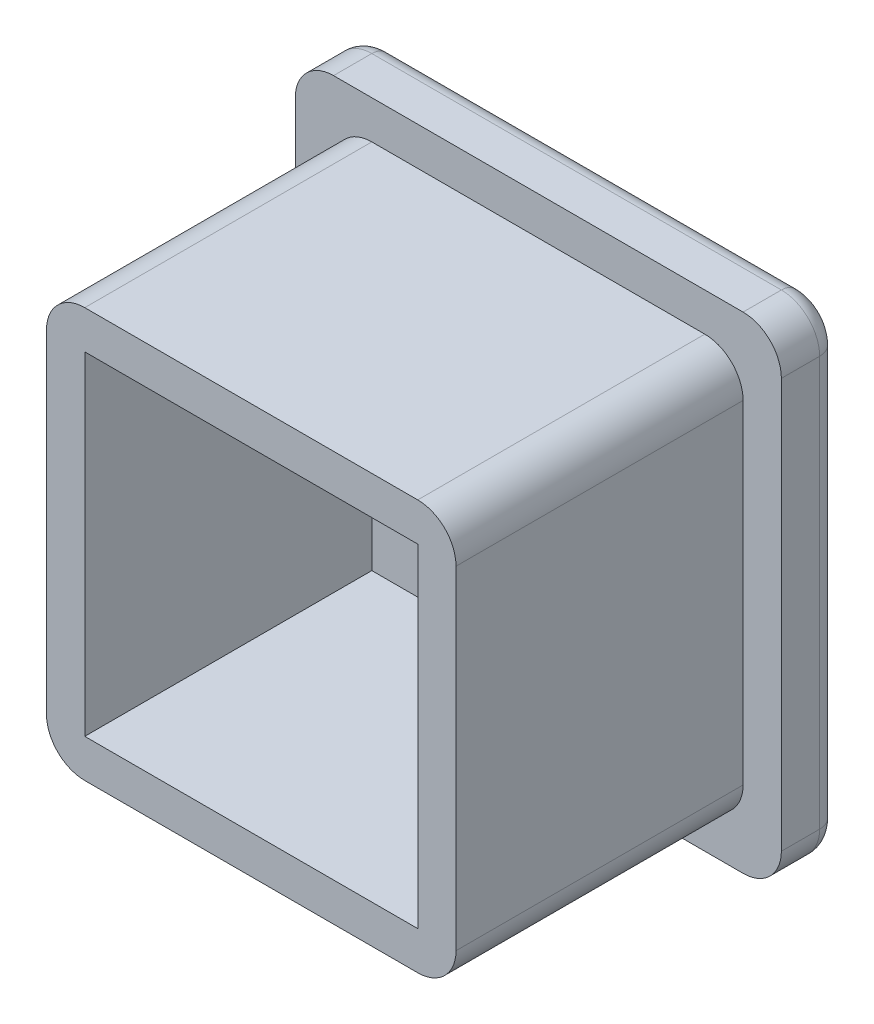
SolidWorks part; units mm, degrees
material "PLA"
ref_plane "Alzado" through (0, 0, 0) normal (0, 0, 1) x (1, 0, 0)
ref_plane "Planta" through (0, 0, 0) normal (0, 1, 0) x (1, 0, 0)
ref_plane "Vista lateral" through (0, 0, 0) normal (1, 0, 0) x (0, 0, -1)
sketch "Croquis1" plane through (0, 0, 0) normal (0, 0, 1) x (1, 0, 0)
  line L1 (12.7, 12.7) -> (-12.7, 12.7)
  line L2 (12.7, 12.7) -> (12.7, -12.7)
  line L3 (12.7, -12.7) -> (-12.7, -12.7)
  line L4 (-12.7, 12.7) -> (-12.7, -12.7)
  line L5 (12.7, 12.7) -> (-12.7, -12.7) construction
  line L6 (12.7, -12.7) -> (-12.7, 12.7) construction
  point P0 (0, 0)
  dimension "D1" = 25.4
  dimension "D2" = 25.4
extrude "Saliente-Extruir1" add sketch "Croquis1" along normal blind 18
sketch "Croquis2" plane through (0, 0, 18) normal (0, 0, 1) x (1, 0, 0)
  line L0 (12.7, 12.7) -> (-12.7, 12.7) construction
  line L1 (-10.7, 10.7) -> (10.7, 10.7)
  line L2 (-10.7, 10.7) -> (-10.7, -10.7)
  line L3 (-10.7, -10.7) -> (10.7, -10.7)
  line L4 (10.7, 10.7) -> (10.7, -10.7)
  line L5 (-12.7, -12.7) -> (12.7, -12.7) construction
  line L6 (-12.7, 12.7) -> (-12.7, -12.7) construction
  line L7 (12.7, -12.7) -> (12.7, 12.7) construction
  line L9 (-12.7, 12.7) -> (12.7, 12.7)
  line L10 (-12.7, 12.7) -> (-12.7, -12.7)
  line L11 (-12.7, -12.7) -> (12.7, -12.7)
  line L12 (12.7, 12.7) -> (12.7, -12.7)
  line L13 (-8.7, 8.7) -> (8.7, 8.7)
  line L14 (-8.7, 8.7) -> (-8.7, -8.7)
  line L15 (-8.7, -8.7) -> (8.7, -8.7)
  line L16 (8.7, 8.7) -> (8.7, -8.7)
  line M9 (-12.7, 12.7) -> (-12.7, -12.7)
  line M10 (-12.7, -12.7) -> (12.7, -12.7)
  line M11 (12.7, -12.7) -> (12.7, 12.7)
  line M12 (12.7, 12.7) -> (-12.7, 12.7)
  dimension "D1" = 2
  dimension "D2" = 2
  dimension "D3" = 2
  dimension "D4" = 2
  dimension "D5" = 4
  dimension "D6" = 4
  dimension "D7" = 4
  dimension "D8" = 4
extrude "Cortar-Extruir1" cut sketch "Croquis2" against normal blind 15 contours L1 L4 L3 L2 M12 M9 M10 M11 | L16 L13 L14 L15
sketch "Croquis3" plane through (0, 0, 18) normal (0, 0, 1) x (1, 0, 0)
  line L0 (-10.7, 10.7) -> (-10.7, -10.7) construction
  line L1 (-10.7, -1.3) -> (-8.7, -1.3)
  line L2 (-10.7, -1.3) -> (-10.7, 1.3)
  line L3 (-10.7, 1.3) -> (-8.7, 1.3)
  line L4 (-8.7, -1.3) -> (-8.7, 1.3)
  line L5 (-8.7, 8.7) -> (-8.7, -8.7) construction
  line L6 (-8.7, -8.7) -> (8.7, -8.7) construction
  line L7 (1.3, -8.7) -> (9.3837, -8.7)
  line L8 (1.3, -8.7) -> (1.3, -10.7)
  line L9 (1.3, -10.7) -> (9.3837, -10.7)
  line L10 (9.3837, -8.7) -> (9.3837, -10.7)
  line L11 (-10.7, -10.7) -> (10.7, -10.7) construction
  line L12 (8.7, 8.7) -> (8.7, -8.7) construction
  line L13 (8.7, 1.3) -> (10.7, 1.3)
  line L14 (8.7, 1.3) -> (8.7, -1.3)
  line L15 (8.7, -1.3) -> (10.7, -1.3)
  line L16 (10.7, 1.3) -> (10.7, -1.3)
  line L17 (10.7, 10.7) -> (10.7, -10.7) construction
  line L18 (-10.7, 10.7) -> (10.7, 10.7) construction
  line L19 (1.3, 10.7) -> (-1.3, 10.7)
  line L20 (1.3, 10.7) -> (1.3, 8.7)
  line L21 (1.3, 8.7) -> (-1.3, 8.7)
  line L22 (-1.3, 10.7) -> (-1.3, 8.7)
  line L23 (-8.7, 8.7) -> (8.7, 8.7) construction
  line L24 (-8.7, 8.7) -> (-8.7, -8.7) construction
  line L25 (8.7, 8.7) -> (8.7, -8.7) construction
  dimension "D1" = 10
  dimension "D2" = 10
  dimension "D3" = 10
  dimension "D4" = 10
  dimension "D5" = 10
  dimension "D6" = 10
  dimension "D7" = 10
extrude "Cortar-Extruir2" [suppressed] cut sketch "Croquis3" against normal blind 7
fillet "Redondeo1" [suppressed] radius 2
fillet "Redondeo2" [suppressed] radius 1
sketch "Croquis5" [suppressed] plane through (0, -38.1, 0) normal (0, -1, 0) x (1, 0, 0)
  line L0 (-23.4, 3) -> (23.4, 3) construction
  line L1 (-3, 3) -> (3, 3)
  line L2 (-3, 3) -> (-3, 1.5)
  line L3 (-3, 1.5) -> (3, 1.5)
  line L4 (3, 3) -> (3, 1.5)
  line L5 (0, 1) -> (0, 3) construction
  line L6 (-23.4, 1) -> (23.4, 1) construction
  dimension "D1" = 3
  dimension "D2" = 3
  dimension "D3" = 1.5
extrude "Cortar-Extruir4" [suppressed] cut sketch "Croquis5" against normal blind 6
sketch "Croquis6" plane through (0, 0, 18) normal (0, 0, 1) x (1, 0, 0)
  line L0 (-10.7, 10.7) -> (4.3, 10.7)
  line L1 (-10.7, 10.7) -> (10.7, 10.7) construction
  line L2 (4.3, 10.7) -> (4.3, 8.7)
  line L3 (-8.7, 8.7) -> (8.7, 8.7) construction
  line L4 (4.3, 8.7) -> (-8.7, 8.7)
  line L5 (-8.7, 8.7) -> (-8.7, -4.3)
  line L6 (-8.7, 8.7) -> (-8.7, -8.7) construction
  line L7 (-8.7, -4.3) -> (-10.7, -4.3)
  line L8 (-10.7, 10.7) -> (-10.7, -10.7) construction
  line L9 (-10.7, -4.3) -> (-10.7, 10.7)
  line L10 (10.7, 10.7) -> (-4.3, 10.7)
  line L11 (-10.7, 10.7) -> (10.7, 10.7) construction
  line L12 (-4.3, 10.7) -> (-4.3, 8.7)
  line L13 (-4.3, 8.7) -> (8.7, 8.7)
  line L14 (8.7, 8.7) -> (8.7, -8.7) construction
  line L15 (8.7, 8.7) -> (8.7, -8.7) construction
  line L16 (8.7, 8.7) -> (8.7, -4.3)
  line L17 (8.7, -4.3) -> (10.7, -4.3)
  line L18 (10.7, 10.7) -> (10.7, -10.7) construction
  line L19 (10.7, -4.3) -> (10.7, 10.7)
  line L20 (-10.7, -10.7) -> (-10.7, 4.3)
  line L21 (-10.7, 10.7) -> (-10.7, -10.7) construction
  line L22 (-10.7, 4.3) -> (-8.7, 4.3)
  line L23 (-8.7, 8.7) -> (-8.7, -8.7) construction
  line L24 (-8.7, 4.3) -> (-8.7, -8.7)
  line L25 (-8.7, -8.7) -> (4.3, -8.7)
  line L26 (-8.7, -8.7) -> (8.7, -8.7) construction
  line L27 (4.3, -8.7) -> (4.3, -10.7)
  line L28 (-10.7, -10.7) -> (10.7, -10.7) construction
  line L29 (4.3, -10.7) -> (-10.7, -10.7)
  line L30 (10.7, -10.7) -> (-4.3, -10.7)
  line L31 (-10.7, -10.7) -> (10.7, -10.7) construction
  line L32 (-4.3, -10.7) -> (-4.3, -8.7)
  line L33 (-8.7, -8.7) -> (8.7, -8.7) construction
  line L34 (-4.3, -8.7) -> (8.7, -8.7)
  line L35 (8.7, -8.7) -> (8.7, 4.3)
  line L36 (8.7, 4.3) -> (10.7, 4.3)
  line L37 (10.7, 10.7) -> (10.7, -10.7) construction
  line L38 (10.7, 4.3) -> (10.7, -10.7)
  dimension "D1" = 15
  dimension "D2" = 15
  dimension "D3" = 15
  dimension "D4" = 15
  dimension "D5" = 15
  dimension "D6" = 15
  dimension "D7" = 15
  dimension "D8" = 15
extrude "Cortar-Extruir8" [suppressed] cut sketch "Croquis6" against normal blind 15
sketch "Croquis10" [suppressed] plane through (0, -20.76, 0) normal (0, -1, 0) x (-1, 0, 0)
  line L0 (23.06, -18) -> (24.06, -18)
  line L1 (24.06, -18) -> (23.06, -3)
  line L2 (23.06, -3) -> (23.06, -18)
  line L3 (-23.06, -18) -> (-24.06, -18)
  line L4 (-24.06, -18) -> (-23.06, -3)
  line L5 (-23.06, -3) -> (-23.06, -18)
  dimension "D1" = 1
  dimension "D2" = 1
extrude "Saliente-Extruir3" [suppressed] add sketch "Croquis10" against normal blind 41.5
sketch "Croquis11" [suppressed] plane through (0, -20.76, 0) normal (0, -1, 0) x (1, 0, 0)
  line L0 (-19.4, 18) -> (-21.56, 18)
  line L1 (-23.06, 18) -> (-24.06, 18) construction
  line L2 (-21.56, 18) -> (-20.56, 3)
  line L3 (-19.4, 3) -> (-23.06, 3) construction
  line L4 (-20.56, 3) -> (-19.4, 3)
  line L5 (-19.4, 18) -> (-19.4, 3)
  dimension "D1" = 2.5
  dimension "D2" = 1.16
extrude "Cortar-Extruir9" [suppressed] cut sketch "Croquis11" against normal blind 51.5
sketch "Croquis12" [suppressed] plane through (0, -20.76, 0) normal (0, -1, 0) x (1, 0, 0)
  line L0 (19.4, 18) -> (19.4, 3)
  line L1 (19.4, 3) -> (20.56, 3)
  line L2 (23.06, 3) -> (19.4, 3) construction
  line L3 (20.56, 3) -> (21.56, 18)
  line L4 (24.06, 18) -> (23.06, 18) construction
  line L5 (21.56, 18) -> (19.4, 18)
  dimension "D1" = 2.5
  dimension "D2" = 1.16
extrude "Cortar-Extruir10" [suppressed] cut sketch "Croquis12" against normal blind 51.5
sketch "Croquis13" [suppressed] plane through (8.06, 0, 0) normal (1, 0, 0) x (0, 0, -1)
  line L0 (-18, -35.76) -> (-18, -37.76)
  line L1 (-18, -37.76) -> (-3, -35.76)
  line L2 (-3, -35.76) -> (-18, -35.76)
  line L3 (-18, 35.76) -> (-18, 37.76)
  line L4 (-18, 37.76) -> (-3, 35.76)
  line L5 (-3, 35.76) -> (-18, 35.76)
  dimension "D1" = 2
  dimension "D2" = 2
extrude "Saliente-Extruir4" [suppressed] add sketch "Croquis13" against normal blind 16
sketch "Croquis14" [suppressed] plane through (8.06, 0, 0) normal (1, 0, 0) x (0, 0, -1)
  line L0 (-3, -32.1) -> (-18, -32.1)
  line L1 (-18, -32.1) -> (-18, -35.26)
  line L2 (-18, -35.76) -> (-18, -37.76) construction
  line L3 (-18, -35.26) -> (-3, -33.26)
  line L4 (-3, -32.1) -> (-3, -35.76) construction
  line L5 (-3, -33.26) -> (-3, -32.1)
  line L6 (-18, 32.1) -> (-18, 35.26)
  line L7 (-18, 37.76) -> (-18, 35.76) construction
  line L8 (-18, 35.26) -> (-3, 33.26)
  line L9 (-3, 35.76) -> (-3, 32.1) construction
  line L10 (-3, 33.26) -> (-3, 32.1)
  line L11 (-3, 32.1) -> (-18, 32.1)
  dimension "D1" = 2.5
  dimension "D2" = 1.16
  dimension "D3" = 2.5
  dimension "D4" = 1.16
extrude "Cortar-Extruir11" [suppressed] cut sketch "Croquis14" against normal blind 16.5
fillet "Redondeo3" radius 2 8 edges at (12.7, 12.7, 1.5) (-12.7, 12.7, 1.5) (-12.7, -12.7, 1.5) (12.7, -12.7, 1.5) (10.7, 10.7, 10.5) (10.7, -10.7, 10.5) (-10.7, -10.7, 10.5) (-10.7, 10.7, 10.5)
fillet "Redondeo4" radius 1 8 edges at (-12.1142, 12.1142, 0) (-12.7, 0, 0) (-12.1142, -12.1142, 0) (0, -12.7, 0) (12.1142, -12.1142, 0) (12.7, 0, 0) (12.1142, 12.1142, 0) (0, 12.7, 0)
sketch "Croquis15" [suppressed] plane through (0, 0, 18) normal (0, 0, 1) x (1, 0, 0)
  line L0 (-24.06, -0.01) -> (24.06, -0.01) construction
  line L1 (-24.06, 20.74) -> (-24.06, -20.76) construction
  line L2 (24.06, 20.74) -> (24.06, -20.76) construction
  line L4 (-24.06, 4.99) -> (24.06, 4.99)
  line L5 (-24.06, 4.99) -> (-24.06, -5.01)
  line L6 (-24.06, -5.01) -> (24.06, -5.01)
  line L7 (24.06, 4.99) -> (24.06, -5.01)
  dimension "D1" = 5
  dimension "D2" = 5
extrude "Cortar-Extruir12" [suppressed] cut sketch "Croquis15" against normal blind 15
sketch "Croquis16" plane through (0, -12.7, 0) normal (0, -1, 0) x (1, 0, 0)
  line L0 (-10.7, 3) -> (10.7, 3) construction
  line L1 (-4, 3) -> (4, 3)
  line L2 (-4, 3) -> (-4, 1.5)
  line L3 (-4, 1.5) -> (4, 1.5)
  line L4 (4, 3) -> (4, 1.5)
  dimension "D1" = 1.5
  dimension "D2" = 8
  dimension "D3" = 4
extrude "Cortar-Extruir13" cut sketch "Croquis16" against normal blind 2
sketch "Croquis17" plane through (0, 0, 3) normal (0, 0, 1) x (1, 0, 0)
  line L0 (-12.7, 10.7) -> (-12.7, -10.7) construction
  line L1 (-10.7, -12.7) -> (-4, -12.7) construction
  circle A0 centre (-0.7, 2.3) radius 3
  dimension "D2" = 6
  dimension "D1" = 12
  dimension "D3" = 15
extrude "Cortar-Extruir14" [suppressed] cut sketch "Croquis17" against normal blind 10
